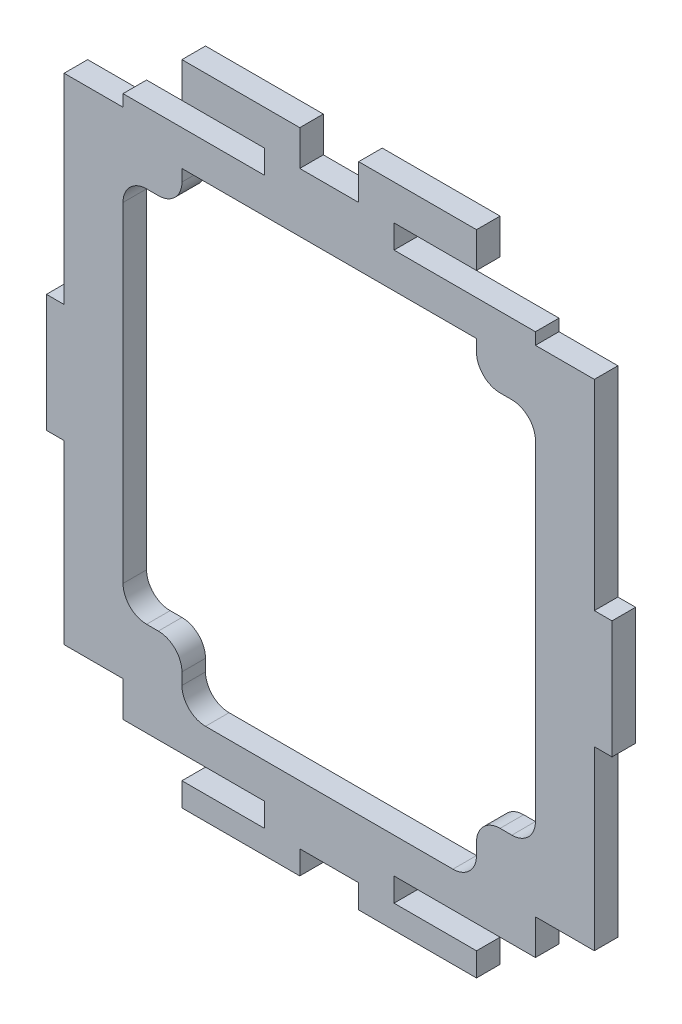
SolidWorks part; units mm, degrees
ref_plane "前视基准面" through (0, 0, 0) normal (0, 0, 1) x (1, 0, 0)
ref_plane "上视基准面" through (0, 0, 0) normal (0, 1, 0) x (1, 0, 0)
ref_plane "右视基准面" through (0, 0, 0) normal (1, 0, 0) x (0, 0, -1)
sketch "Model" plane through (0, 0, 0) normal (0, 0, 1) x (1, 0, 0)
  line L0 (1228.5095, 484.7216) -> (1228.5095, 467.7216)
  line L1 (1228.5095, 457.7216) -> (1228.5095, 442.7216)
  line L2 (1227.0095, 467.7216) -> (1228.5095, 467.7216)
  line L3 (1227.0095, 457.7216) -> (1228.5095, 457.7216)
  line L4 (1233.5095, 484.7216) -> (1233.5095, 485.7216)
  line L5 (1228.5095, 442.7216) -> (1233.5095, 442.7216)
  line L6 (1233.5095, 442.7216) -> (1233.5095, 439.7216)
  line L7 (1227.0095, 467.7216) -> (1227.0095, 457.7216)
  line L8 (1253.5095, 487.7216) -> (1248.5095, 487.7216)
  line L9 (1248.5095, 490.7216) -> (1238.5095, 490.7216)
  line L10 (1238.5095, 487.7216) -> (1238.5095, 490.7216)
  line L11 (1248.5095, 490.7216) -> (1248.5095, 487.7216)
  line L12 (1253.5095, 437.7216) -> (1248.5095, 437.7216)
  line L13 (1248.5095, 435.7216) -> (1238.5095, 435.7216)
  line L14 (1238.5095, 437.7216) -> (1238.5095, 435.7216)
  line L15 (1248.5095, 435.7216) -> (1248.5095, 437.7216)
  line L16 (1235.5095, 479.7216) -> (1236.5095, 479.7216)
  line L17 (1238.5095, 481.7216) -> (1238.5095, 482.7216)
  line L18 (1235.5095, 447.7216) -> (1236.5095, 447.7216)
  line L19 (1238.5095, 445.7216) -> (1238.5095, 444.7216)
  line L20 (1240.5095, 442.7216) -> (1261.5095, 442.7216)
  line L21 (1273.5095, 484.7216) -> (1273.5095, 467.7216)
  line L22 (1273.5095, 457.7216) -> (1273.5095, 442.7216)
  line L23 (1275.0095, 467.7216) -> (1273.5095, 467.7216)
  line L24 (1273.5095, 484.7216) -> (1268.5095, 484.7216)
  line L25 (1268.5095, 484.7216) -> (1268.5095, 485.7216)
  line L26 (1273.5095, 442.7216) -> (1268.5095, 442.7216)
  line L27 (1268.5095, 442.7216) -> (1268.5095, 439.7216)
  line L28 (1253.5095, 490.7216) -> (1263.5095, 490.7216)
  line L29 (1263.5095, 487.7216) -> (1263.5095, 490.7216)
  line L30 (1253.5095, 490.7216) -> (1253.5095, 487.7216)
  line L31 (1253.5095, 435.7216) -> (1263.5095, 435.7216)
  line L32 (1263.5095, 437.7216) -> (1263.5095, 435.7216)
  line L33 (1253.5095, 435.7216) -> (1253.5095, 437.7216)
  line L34 (1266.5095, 479.7216) -> (1265.5095, 479.7216)
  line L35 (1263.5095, 481.7216) -> (1263.5095, 482.7216)
  line L36 (1266.5095, 447.7216) -> (1265.5095, 447.7216)
  line L37 (1263.5095, 445.7216) -> (1263.5095, 444.7216)
  line L38 (1268.5095, 477.7216) -> (1268.5095, 449.7216)
  line L39 (1233.5095, 477.7216) -> (1233.5095, 449.7216)
  line L40 (1275.0095, 457.7216) -> (1273.5095, 457.7216)
  line L41 (1238.5095, 487.7216) -> (1245.5095, 487.7216)
  line L42 (1245.5095, 485.7216) -> (1233.5095, 485.7216)
  line L43 (1263.5095, 487.7216) -> (1256.5095, 487.7216)
  line L44 (1233.5095, 439.7216) -> (1245.5095, 439.7216)
  line L45 (1256.5095, 439.7216) -> (1268.5095, 439.7216)
  line L46 (1238.5095, 482.7216) -> (1263.5095, 482.7216)
  line L47 (1228.5095, 484.7216) -> (1233.5095, 484.7216)
  line L48 (1245.5095, 485.7216) -> (1245.5095, 487.7216)
  line L49 (1256.5095, 485.7216) -> (1268.5095, 485.7216)
  line L50 (1256.5095, 485.7216) -> (1256.5095, 487.7216)
  line L51 (1238.5095, 437.7216) -> (1245.5095, 437.7216)
  line L52 (1263.5095, 437.7216) -> (1256.5095, 437.7216)
  line L53 (1245.5095, 439.7216) -> (1245.5095, 437.7216)
  line L54 (1256.5095, 439.7216) -> (1256.5095, 437.7216)
  line L55 (1275.0095, 467.7216) -> (1275.0095, 457.7216)
  arc A0 (1238.5095, 444.7216) -> (1240.5095, 442.7216) centre (1240.5095, 444.7216) ccw
  arc A1 (1235.5095, 479.7216) -> (1233.5095, 477.7216) centre (1235.5095, 477.7216) ccw
  arc A2 (1236.5095, 479.7216) -> (1238.5095, 481.7216) centre (1236.5095, 481.7216) ccw
  arc A3 (1233.5095, 449.7216) -> (1235.5095, 447.7216) centre (1235.5095, 449.7216) ccw
  arc A4 (1238.5095, 445.7216) -> (1236.5095, 447.7216) centre (1236.5095, 445.7216) ccw
  arc A5 (1261.5095, 442.7216) -> (1263.5095, 444.7216) centre (1261.5095, 444.7216) ccw
  arc A6 (1268.5095, 477.7216) -> (1266.5095, 479.7216) centre (1266.5095, 477.7216) ccw
  arc A7 (1263.5095, 481.7216) -> (1265.5095, 479.7216) centre (1265.5095, 481.7216) ccw
  arc A8 (1266.5095, 447.7216) -> (1268.5095, 449.7216) centre (1266.5095, 449.7216) ccw
  arc A9 (1265.5095, 447.7216) -> (1263.5095, 445.7216) centre (1265.5095, 445.7216) ccw
extrude "凸台-拉伸1" add sketch "Model" along normal blind 2
